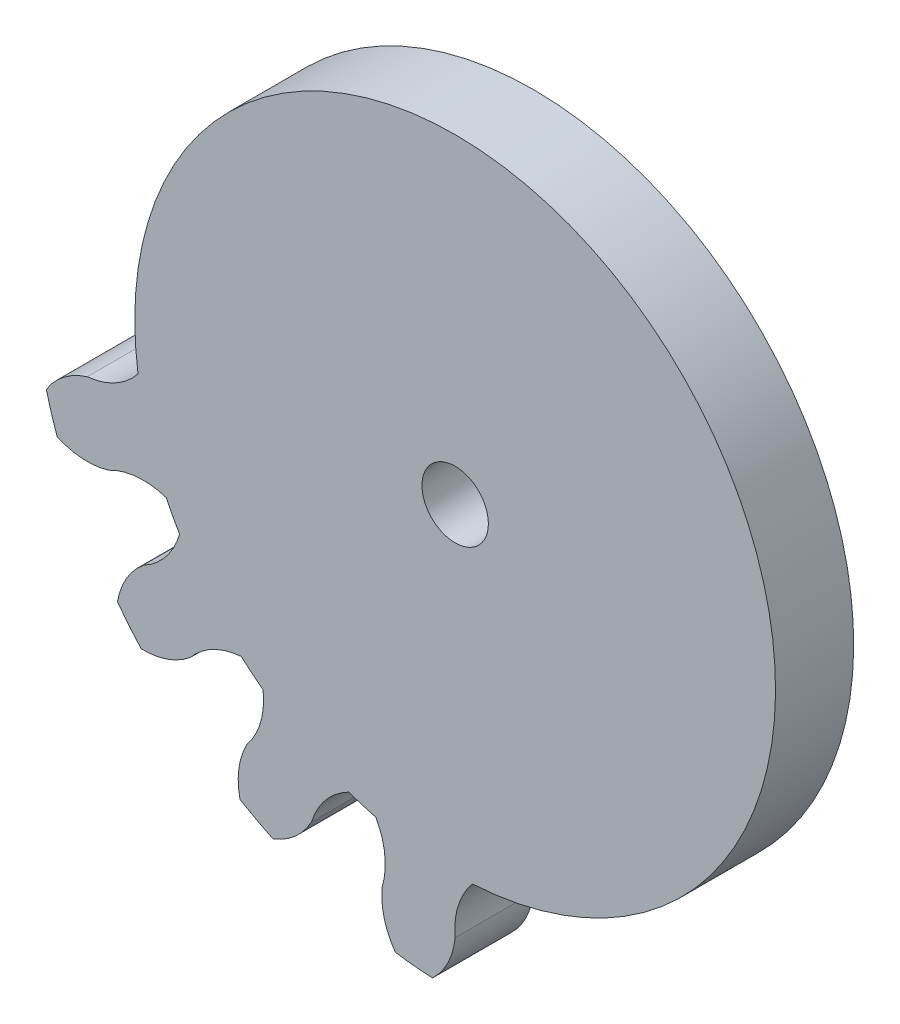
SolidWorks part; units mm, degrees
ref_plane "Front Plane" through (0, 0, 0) normal (0, 0, 1) x (1, 0, 0)
ref_plane "Top Plane" through (0, 0, 0) normal (0, 1, 0) x (1, 0, 0)
ref_plane "Right Plane" through (0, 0, 0) normal (1, 0, 0) x (0, 0, -1)
sketch "Sketch1" plane through (0, 0, 0) normal (0, 0, 1) x (1, 0, 0)
  circle A0 centre (0, 0) radius 54
  dimension "D1" = 108
extrude "Boss-Extrude1" add sketch "Sketch1" along normal blind 10
sketch "Sketch2" plane through (0, 0, 10) normal (0, 0, 1) x (1, 0, 0)
  line L0 (0, 0) -> (0, 48) construction
  arc A9 (-2.2265, 40.9375) -> (0, 48) centre (-9.3795, 47.0747) ccw
  arc A12 (-2.2265, 40.9375) -> (-5.8159, 40.5834) centre (0, 0) ccw
  arc A13 (2.9029, 53.9219) -> (-13.3836, 52.3152) centre (0, 0) ccw
  arc A14 (-9.3795, 47.0747) -> (-5.8159, 40.5834) centre (0, 48) ccw
  arc A15 (2.9029, 53.9219) -> (0, 48) centre (9.3795, 47.0747) ccw
  arc A18 (-9.3795, 47.0747) -> (-13.3836, 52.3152) centre (-18.3973, 44.3344) ccw
extrude "Cut-Extrude1" cut sketch "Sketch2" against normal blind 10
pattern_circular "CirPattern1" count 16 over 360 about axis through (0, 0, 0) along (0, 0, 1) of "Cut-Extrude1"
sketch "Sketch4" plane through (0, 0, 10) normal (0, 0, 1) x (1, 0, 0)
  line L0 (-5.6721, 53.7013) -> (5.6721, -53.7013) construction
  line L2 (4.3064, -40.7712) -> (5.6721, -53.7013)
  line L8 (-40.7999, -4.0251) -> (-53.7391, -5.3016)
  arc A2 (4.3064, -40.7712) -> (-31.6961, 26.0038) centre (0, 0) ccw
  arc A4 (4.3064, -40.7712) -> (-40.7999, -4.0251) centre (0, 0) ccw
  arc A5 (5.6721, -53.7013) -> (-53.7391, -5.3016) centre (0, 0) ccw
extrude "Cut-Extrude2" cut sketch "Sketch4" against normal blind 10 contours L0 A5 L8 A4 | A5 L0 A2 L2
sketch "Sketch5" plane through (0, 0, 10) normal (0, 0, 1) x (1, 0, 0)
  circle A0 centre (0, 0) radius 4.25
  dimension "D1" = 8.5
extrude "Cut-Extrude3" cut sketch "Sketch5" against normal blind 10
